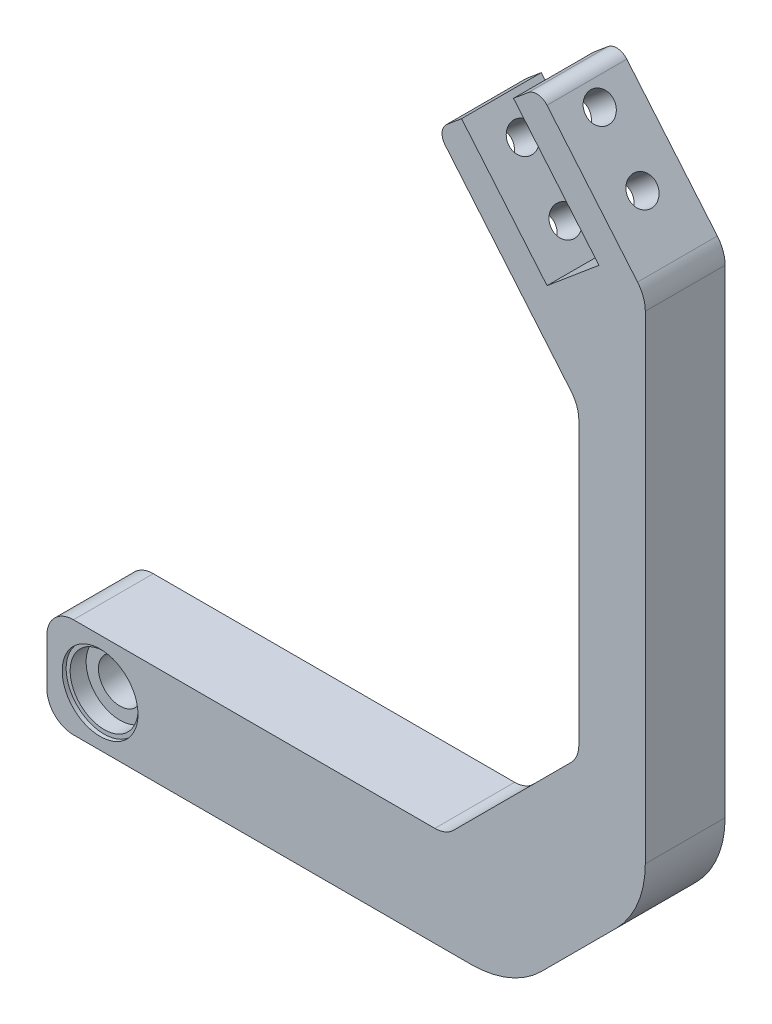
SolidWorks part; units mm, degrees
ref_plane "前视基准面" through (0, 0, 0) normal (0, 0, 1) x (1, 0, 0)
ref_plane "上视基准面" through (0, 0, 0) normal (0, 1, 0) x (1, 0, 0)
ref_plane "右视基准面" through (0, 0, 0) normal (1, 0, 0) x (0, 0, -1)
other "Configuration Table"
sketch "草图1" plane through (0, 0, 0) normal (0, 0, 1) x (1, 0, 0)
  line L0 (0, 0) -> (15.3209, 12.8558)
  line L1 (15.3209, 12.8558) -> (31.3906, -6.2954)
  line L2 (31.3906, -6.2954) -> (31.3906, -106.2954)
  line L3 (31.3906, -106.2954) -> (-58.6094, -106.2954)
  line L4 (-58.6094, -106.2954) -> (-58.6094, -91.2954)
  line L5 (-58.6094, -91.2954) -> (21.3906, -91.2954)
  line L6 (21.3906, -91.2954) -> (21.3906, -25.4923)
  line L7 (21.3906, -25.4923) -> (0, 0)
  dimension "D1" = 15
  dimension "D2" = 10
  dimension "D3" = 80
  dimension "D4" = 20
  dimension "D5" = 140
  dimension "D6" = 25
  dimension "D7" = 100
extrude "凸台-拉伸1" add sketch "草图1" along normal mid plane 12
sketch "草图2" plane through (0, 0, 6) normal (0, 0, 1) x (1, 0, 0)
  line L0 (3.7536, 3.1497) -> (16.6094, -12.1712)
  line L1 (15.3209, 12.8558) -> (0, 0) construction
  line L2 (16.6094, -12.1712) -> (24.423, -5.6148)
  line L3 (24.423, -5.6148) -> (11.5673, 9.7061)
  line L4 (11.5673, 9.7061) -> (3.7536, 3.1497)
  point P4 (7.6604, 6.4279)
  dimension "D1" = 10.2
  dimension "D2" = 20
extrude "切除-拉伸1" cut sketch "草图2" against normal through all
sketch "草图3" plane through (0, 0, 6) normal (0, 0, 1) x (1, 0, 0)
  line L0 (-58.6094, -91.2954) -> (-58.6094, -106.2954) construction
  line L1 (-50.6094, -98.7954) -> (-58.6094, -98.7954) construction
  circle A0 centre (-50.6094, -98.7954) radius 3.25
  dimension "D1" = 6.5
  dimension "D2" = 8
extrude "切除-拉伸2" cut sketch "草图3" against normal through all
sketch "草图4" plane through (15.3209, 12.8558, 0) normal (0.766, 0.6428, 0) x (0, 0, -1)
  line L0 (-6, 0) -> (6, 0) construction
  line L2 (0, 0) -> (0, -5) construction
  circle A0 centre (0, -5) radius 2.1
  circle A1 centre (0, -15) radius 2.1
  dimension "D1" = 10
  dimension "D2" = 4.2
  dimension "D3" = 5
extrude "切除-拉伸3" cut sketch "草图4" against normal through all
chamfer "倒角1" distance 20 angle 45 1 edges at (21.3906, -91.2954, 0)
chamfer "倒角2" distance 20 angle 45 1 edges at (31.3906, -106.2954, 0)
fillet "圆角1" radius 4 4 edges at (21.3906, -71.2954, 0) (1.3906, -91.2954, 0) (-58.6094, -106.2954, 0) (-58.6094, -91.2954, 0)
fillet "圆角2" radius 2 2 edges at (15.3209, 12.8558, 0) (0, 0, 0)
fillet "圆角3" radius 15 2 edges at (31.3906, -86.2954, 0) (11.3906, -106.2954, 0)
sketch "草图5" plane through (0, 0, 6) normal (0, 0, 1) x (1, 0, 0)
  circle A0 centre (-50.6094, -98.7954) radius 5.1
  dimension "D1" = 10.2
extrude "切除-拉伸4" cut sketch "草图5" against normal blind 3
sketch "草图6" plane through (0, 0, -6) normal (0, 0, -1) x (-1, 0, 0)
  circle A0 centre (50.6094, -98.7954) radius 5.1
  dimension "D1" = 10.2
sketch "草图7" plane through (0, 0, 6) normal (0, 0, 1) x (1, 0, 0)
  circle A0 centre (-50.6094, -98.7954) radius 5.7
  dimension "D1" = 11.4
extrude "切除-拉伸6" cut sketch "草图7" against normal blind 0.6
sketch "草图8" plane through (0, 0, -6) normal (0, 0, -1) x (-1, 0, 0)
  circle A0 centre (50.6094, -98.7954) radius 5.1
  dimension "D1" = 10.2
extrude "切除-拉伸7" cut sketch "草图8" against normal blind 3
sketch "草图9" plane through (0, 0, -6) normal (0, 0, -1) x (-1, 0, 0)
  circle A0 centre (50.6094, -98.7954) radius 5.7
  dimension "D1" = 11.4
extrude "切除-拉伸8" cut sketch "草图9" against normal blind 0.6
extrude "切除-拉伸5" cut sketch "草图6" against normal blind 4
fillet "圆角4" radius 5 2 edges at (21.3906, -25.4923, 0) (31.3906, -6.2954, 0)
